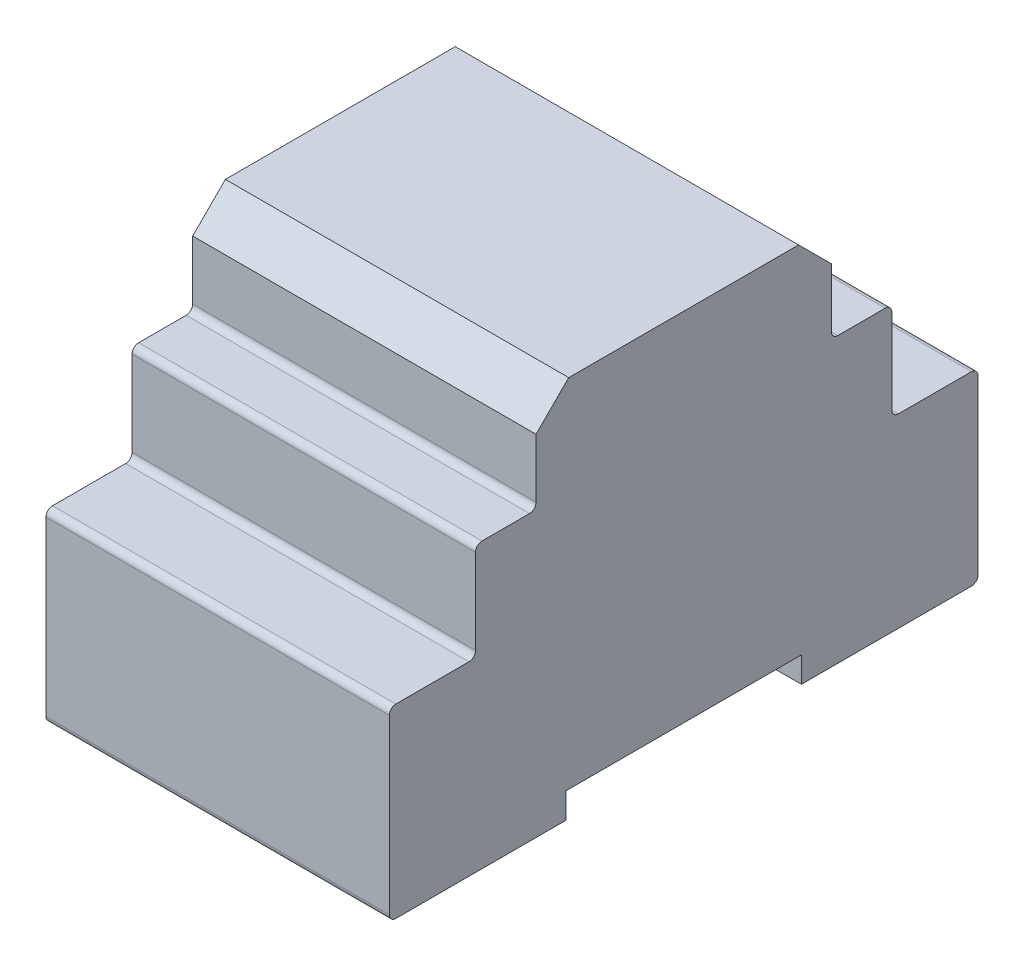
SolidWorks part; units mm, degrees
ref_plane "Front" through (0, 0, 0) normal (0, 0, 1) x (1, 0, 0)
ref_plane "Top" through (0, 0, 0) normal (0, 1, 0) x (1, 0, 0)
ref_plane "Right" through (0, 0, 0) normal (1, 0, 0) x (0, 0, -1)
sketch "Эскиз1" plane through (0, 0, 0) normal (0, 1, 0) x (1, 0, 0)
  line L1 (0, 0) -> (52.5, 0)
  line L2 (0, 0) -> (0, 90)
  line L3 (0, 90) -> (52.5, 90)
  line L4 (52.5, 0) -> (52.5, 90)
  dimension "D1" = 52.5
  dimension "D2" = 90
extrude "Бобышка-Вытянуть1" add sketch "Эскиз1" along normal blind 58.4
sketch "Эскиз3" plane through (0, 58.4, 0) normal (0, 1, 0) x (1, 0, 0)
  line L1 (0, 90) -> (0, 0) construction
  line L2 (0, 90) -> (52.5, 90)
  line L3 (0, 90) -> (0, 67.575)
  line L4 (0, 67.575) -> (52.5, 67.575)
  line L6 (52.5, 90) -> (52.5, 67.575)
  line L7 (52.5, 90) -> (0, 90) construction
  line L8 (52.5, 0) -> (52.5, 90) construction
  line L9 (0, 45) -> (52.5, 45) construction
  line L10 (0, 0) -> (52.5, 0)
  line L11 (0, 0) -> (0, 22.425)
  line L12 (0, 22.425) -> (52.5, 22.425)
  line L13 (52.5, 0) -> (52.5, 22.425)
  dimension "D1" = 45.15
  dimension "D2" = 22.425
extrude "Вырез-Вытянуть1" cut sketch "Эскиз3" against normal blind 15
sketch "Эскиз4" plane through (0, 43.4, 0) normal (0, 1, 0) x (1, 0, 0)
  line L1 (0, 90) -> (52.5, 90)
  line L2 (0, 90) -> (0, 76.82)
  line L3 (0, 76.82) -> (52.5, 76.82)
  line L4 (52.5, 90) -> (52.5, 76.82)
  line L6 (0, 0) -> (52.5, 0)
  line L7 (0, 0) -> (0, 13.17)
  line L8 (0, 13.17) -> (52.5, 13.17)
  line L9 (52.5, 0) -> (52.5, 13.17)
  dimension "D1" = 63.65
  dimension "D2" = 13.18
extrude "Вырез-Вытянуть2" cut sketch "Эскиз4" against normal blind 15
chamfer "Фаска1" distance 5 angle 45 2 edges at (26.25, 58.4, -67.575) (26.25, 58.4, -22.425)
sketch "Эскиз5" plane through (0, 0, 0) normal (0, -1, 0) x (1, 0, 0)
  line L0 (52.5, 0) -> (52.5, -90) construction
  line L1 (52.5, -63) -> (0, -63)
  line L2 (52.5, -63) -> (52.5, -27)
  line L3 (52.5, -27) -> (0, -27)
  line L4 (0, -63) -> (0, -27)
  line L5 (0, -90) -> (0, 0) construction
  line L6 (52.5, -90) -> (0, -90) construction
  dimension "D1" = 36
  dimension "D2" = 27
extrude "Вырез-Вытянуть3" cut sketch "Эскиз5" against normal blind 3.9
fillet "Скругление1" radius 1 10 edges at (26.25, 0, -90) (26.25, 0, 0) (26.25, 28.4, -13.17) (26.25, 28.4, 0) (26.25, 43.4, -13.17) (26.25, 43.4, -22.425) (26.25, 28.4, -90) (26.25, 28.4, -76.82) (26.25, 43.4, -76.82) (26.25, 43.4, -67.575)
